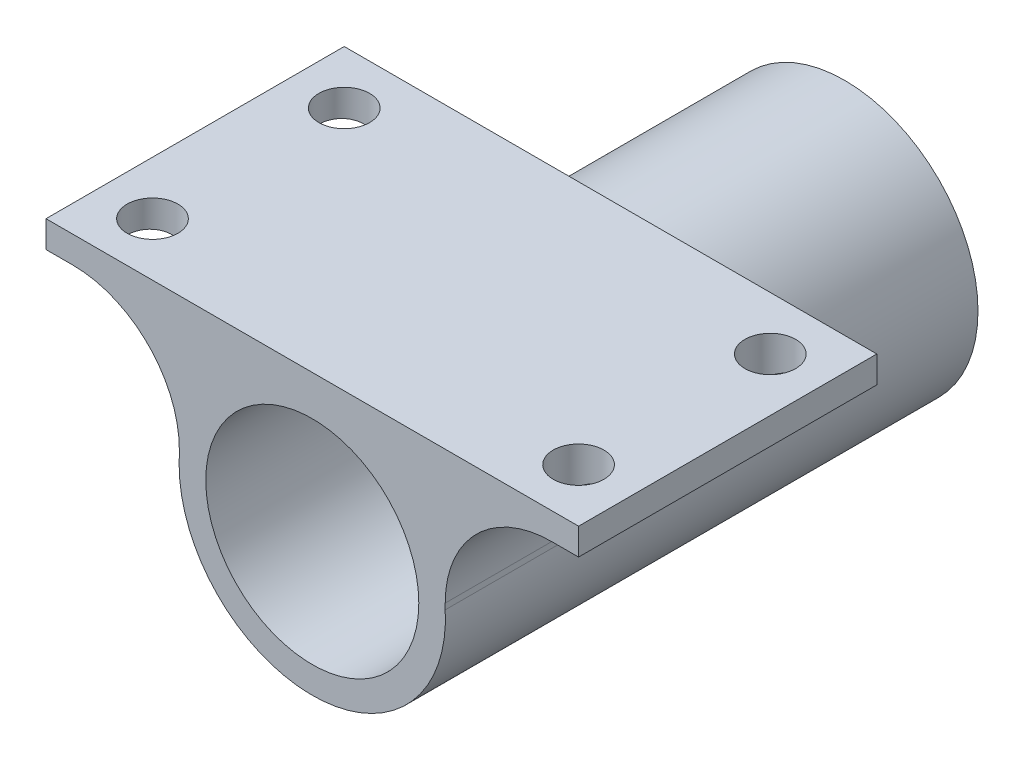
SolidWorks part; units mm, degrees
ref_plane "Front" through (0, 0, 0) normal (0, 0, 1) x (1, 0, 0)
ref_plane "Top" through (0, 0, 0) normal (0, 1, 0) x (1, 0, 0)
ref_plane "Right" through (0, 0, 0) normal (1, 0, 0) x (0, 0, -1)
sketch "Sketch1" plane through (0, 0, 0) normal (0, 0, 1) x (1, 0, 0)
  line L2 (-25, 11.2434) -> (-25, 13.7566)
  line L3 (-25, 13.7566) -> (25, 13.7566)
  line L4 (25, 11.2434) -> (25, 13.7566)
  line L5 (0, 12.5) -> (-25, 12.5) construction
  line L6 (0, 12.5) -> (25, 12.5) construction
  line L7 (25, 11.2434) -> (22.4809, 11.2434)
  line L8 (12.4809, 1.2434) -> (12.4809, 0.6908)
  line L9 (-12.4809, 0.6908) -> (-12.4809, 1.2434)
  line L10 (-22.4809, 11.2434) -> (-25, 11.2434)
  circle A0 centre (0, 0) radius 10
  arc A1 (-12.4809, 0.6908) -> (12.4809, 0.6908) centre (0, 0) ccw
  arc A4 (22.4809, 11.2434) -> (12.4809, 1.2434) centre (22.4809, 1.2434) ccw
  arc A5 (-12.4809, 1.2434) -> (-22.4809, 11.2434) centre (-22.4809, 1.2434) ccw
  point P4 (0, 12.5)
  point P12 (5.4623, 11.2434)
  dimension "D1" = 20
  dimension "D2" = 25
  dimension "D4" = 10
  dimension "D3" = 50
extrude "Boss-Extrude1" add sketch "Sketch1" along normal blind 48 contours L3 L4 A1 L2
sketch "Sketch3" plane through (0, 0, 0) normal (0, 0, -1) x (-1, 0, 0)
  line L0 (-7.5, 0) -> (7.5, 0) construction
  circle A0 centre (0, 0) radius 3.5
  circle A1 centre (0, 0) radius 12.5
  circle A2 centre (7.5, 0) radius 0.95
  circle A3 centre (-7.5, 0) radius 0.95
  dimension "D1" = 7
  dimension "D2" = 25
  dimension "D3" = 1.9
  dimension "D4" = 1.9
  dimension "D5" = 7.5
  dimension "D6" = 7.5
extrude "Boss-Extrude3" add sketch "Sketch3" along normal blind 2
sketch "Sketch4" plane through (0, 13.7566, 0) normal (0, 1, 0) x (1, 0, 0)
  line L0 (25, -48) -> (25, 0) construction
  line L2 (-25, -48) -> (-25, 0) construction
  line L3 (25, -48) -> (-25, -48) construction
  circle A0 centre (-20, -25) radius 2.3813
  circle A1 centre (20, -25) radius 2.3813
  circle A2 centre (20, -43) radius 2.3813
  circle A3 centre (-20, -43) radius 2.3813
  dimension "D2" = 18
  dimension "D3" = 4.7625
  dimension "D4" = 18
  dimension "D5" = 5
  dimension "D7" = 5
  dimension "D9" = 5
  dimension "D10" = 5
  dimension "D11" = 5
  dimension "D12" = 5
extrude "Cut-Extrude1" cut sketch "Sketch4" against normal through all
sketch "Sketch6" plane through (0, 0, -2) normal (0, 0, -1) x (-1, 0, 0)
  line L0 (10.178, -7.2566) -> (29.1547, -20.7862) construction
  line L1 (-29.1547, 20.7862) -> (29.1547, 20.7862)
  line L2 (-29.1547, 20.7862) -> (-29.1547, -20.7862)
  line L3 (-29.1547, -20.7862) -> (29.1547, -20.7862)
  line L4 (29.1547, 20.7862) -> (29.1547, -20.7862)
  line L5 (-29.1547, 20.7862) -> (-10.178, 7.2566) construction
  line L6 (-29.1547, -20.7862) -> (-10.178, -7.2566) construction
  line L7 (10.178, 7.2566) -> (29.1547, 20.7862) construction
  circle A0 centre (0, 0) radius 12.5
  dimension "D1" = 25
extrude "Cut-Extrude4" cut sketch "Sketch6" against normal blind 22
